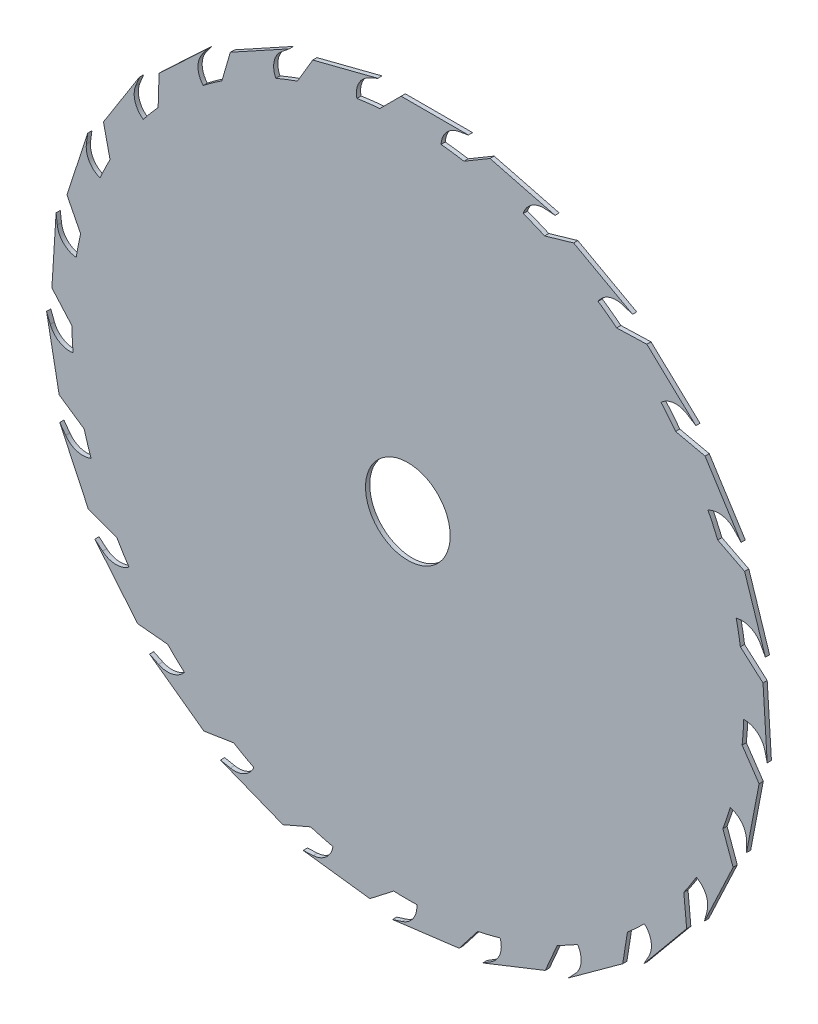
SolidWorks part; units mm, degrees
ref_plane "Front Plane" through (0, 0, 0) normal (0, 0, 1) x (1, 0, 0)
ref_plane "Top Plane" through (0, 0, 0) normal (0, 1, 0) x (1, 0, 0)
ref_plane "Right Plane" through (0, 0, 0) normal (1, 0, 0) x (0, 0, -1)
sketch "Sketch1" plane through (0, 0, 0) normal (0, 0, 1) x (1, 0, 0)
  circle A0 centre (0, 0) radius 127
  dimension "D1" = 254
extrude "Boss-Extrude1" add sketch "Sketch1" along normal blind 1.5875 contours A0
sketch "Sketch2" plane through (0, 0, 1.5875) normal (0, 0, 1) x (1, 0, 0)
  circle A0 centre (0, 0) radius 16.002
  dimension "D1" = 32.004
extrude "Cut-Extrude1" cut sketch "Sketch2" against normal up to next
sketch "Sketch4" plane through (0, 0, 1.5875) normal (0, 0, 1) x (1, 0, 0)
  line L0 (-12.7, 124.46) -> (-2.54, 134.62)
  line L1 (-2.54, 134.62) -> (22.86, 134.62)
  line L2 (22.86, 134.62) -> (19.1129, 133.9305)
  line L3 (12.7, 124.46) -> (-12.7, 124.46)
  arc A0 (19.1129, 133.9305) -> (12.7, 124.46) centre (20.5648, 126.0408) ccw
  point P8 (0, 124.46)
  dimension "D1" = 3.81
  dimension "D7" = 1.5808
  dimension "D2" = 25.4
  dimension "D3" = 10.16
  dimension "D4" = 25.4
  dimension "D5" = 134.62
  dimension "D6" = 45
extrude "Boss-Extrude2" add sketch "Sketch4" against normal up to surface (1.5875 mm away) up to face at (16.002, 0, 0)
pattern_circular "CirPattern1" count 25 over 360 about axis through (0, 0, 0) along (0, 0, 1) of "Boss-Extrude2"
